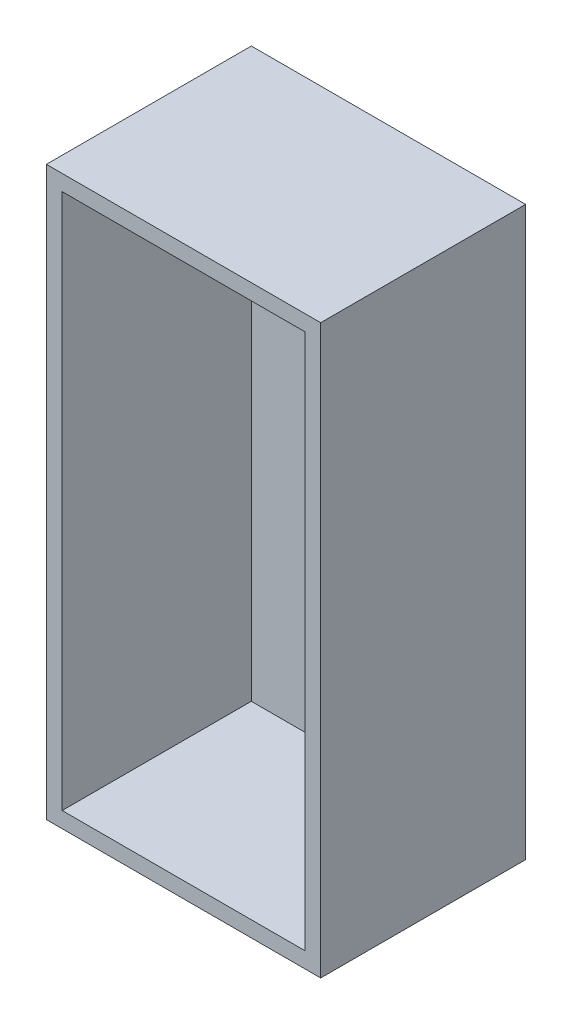
SolidWorks part; units mm, degrees
ref_plane "Front Plane" through (0, 0, 0) normal (1, 0, 0) x (0, 1, 0)
ref_plane "Top Plane" through (0, 0, 0) normal (0, 0, 1) x (0, 1, 0)
ref_plane "Right Plane" through (0, 0, 0) normal (0, 1, 0) x (-1, 0, 0)
sketch "Sketch1" plane through (0, 0, 0) normal (0, 1, 0) x (-1, 0, 0)
  line L1 (-43.5, 32.5) -> (43.5, 32.5)
  line L2 (-43.5, 32.5) -> (-43.5, -32.5)
  line L3 (-43.5, -32.5) -> (43.5, -32.5)
  line L4 (43.5, 32.5) -> (43.5, -32.5)
  line L5 (-43.5, 32.5) -> (43.5, -32.5) construction
  line L6 (-43.5, -32.5) -> (43.5, 32.5) construction
  point P0 (0, 0)
  dimension "D1" = 87
  dimension "D2" = 65
extrude "Boss-Extrude1" add sketch "Sketch1" along normal mid plane 180
shell "Shell1" thickness 5
